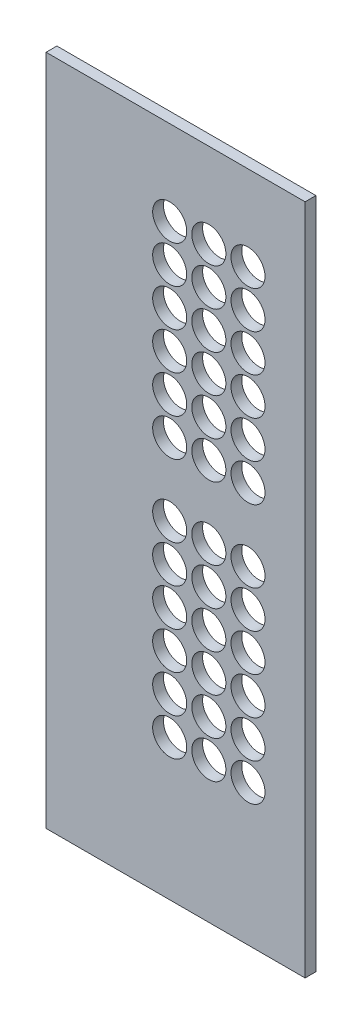
SolidWorks part; units mm, degrees
material "ABS"
ref_plane "X-Y Datum" through (0, 0, 0) normal (0, 0, 1) x (1, 0, 0)
ref_plane "X-Z Datum" through (0, 0, 0) normal (0, 1, 0) x (1, 0, 0)
ref_plane "Y-Z Datum" through (0, 0, 0) normal (1, 0, 0) x (0, 0, -1)
sketch "Sketch1" plane through (0, 0, 0) normal (0, 0, 1) x (1, 0, 0)
  line L1 (-28.275, 98.7125) -> (28.275, 98.7125)
  line L2 (-28.275, 98.7125) -> (-28.275, -98.7125)
  line L3 (-28.275, -98.7125) -> (28.275, -98.7125)
  line L4 (28.275, 98.7125) -> (28.275, -98.7125)
  line L5 (-28.275, 98.7125) -> (28.275, -98.7125) construction
  line L6 (-28.275, -98.7125) -> (28.275, 98.7125) construction
  point P0 (0, 0)
  dimension "D1" = 56.55
  dimension "D2" = 197.425
extrude "Boss-Extrude1" add sketch "Sketch1" along normal blind 3.175
sketch "Sketch2" plane through (0, 0, 0) normal (0, 0, -1) x (-1, 0, 0)
  line L0 (0, -98.7125) -> (0, 98.7125) construction
  line L1 (28.275, -98.7125) -> (-28.275, -98.7125) construction
  line L2 (-28.275, 98.7125) -> (28.275, 98.7125) construction
  line L3 (11.5, -57.3692) -> (-11.5, -57.3692) construction
  line L4 (-14.3429, -63.3692) -> (21.6571, -63.3692) construction
  line L5 (11.5, 18.8308) -> (-11.5, 18.8308) construction
  line L6 (-14.3429, 12.8308) -> (21.6571, 12.8308) construction
  circle A0 centre (11.5, -57.3692) radius 5
  circle A1 centre (-11.5, -57.3692) radius 5
  circle A2 centre (0, -57.3692) radius 5
  circle A3 centre (0, 18.8308) radius 5
  circle A4 centre (-11.5, 18.8308) radius 5
  circle A5 centre (11.5, 18.8308) radius 5
  point P12 (0, -57.3692)
  point P21 (0, 18.8308)
  dimension "D1" = 10
  dimension "D2" = 23
  dimension "D3" = 6
  dimension "D4" = 6
extrude "Cut-Extrude1" cut sketch "Sketch2" against normal blind 10 contours A0 | A1 | A5 | A3 | A4 | A2
pattern_linear "LPattern1" count 6 spacing 11 along (0, 1, 0) of "Cut-Extrude1"
sketch "Sketch4" [suppressed] plane through (0, 0, 3.175) normal (0, 0, 1) x (1, 0, 0)
  circle A5 centre (0, -57.3692) radius 5
  circle A6 centre (0, -57.3692) radius 5
  circle A7 centre (11.5, -57.3692) radius 5
  circle A8 centre (11.5, -57.3692) radius 5
  circle A9 centre (-11.5, -57.3692) radius 5
  circle A10 centre (-11.5, -57.3692) radius 5
  dimension "D3" = 0
  dimension "D4" = 0
  dimension "D5" = 0
extrude "Cut-Extrude2" [suppressed] cut sketch "Sketch4" against normal through all
pattern_linear "LPattern3" [suppressed] count 13 spacing 11
sketch "Sketch5" plane through (-28.275, 0, 0) normal (-1, 0, 0) x (0, 0, 1)
  line L4 (0, 98.7125) -> (0, -98.7125)
  line L5 (0, -98.7125) -> (3.175, -98.7125)
  line L6 (3.175, -98.7125) -> (3.175, 98.7125)
  line L7 (3.175, 98.7125) -> (0, 98.7125)
  line L8 (0, 98.7125) -> (0, -98.7125)
  line L9 (0, -98.7125) -> (3.175, -98.7125)
  line L10 (3.175, -98.7125) -> (3.175, 98.7125)
  line L11 (3.175, 98.7125) -> (0, 98.7125)
  dimension "D1" = 0
extrude "Boss-Extrude2" add sketch "Sketch5" along normal blind 19.525
